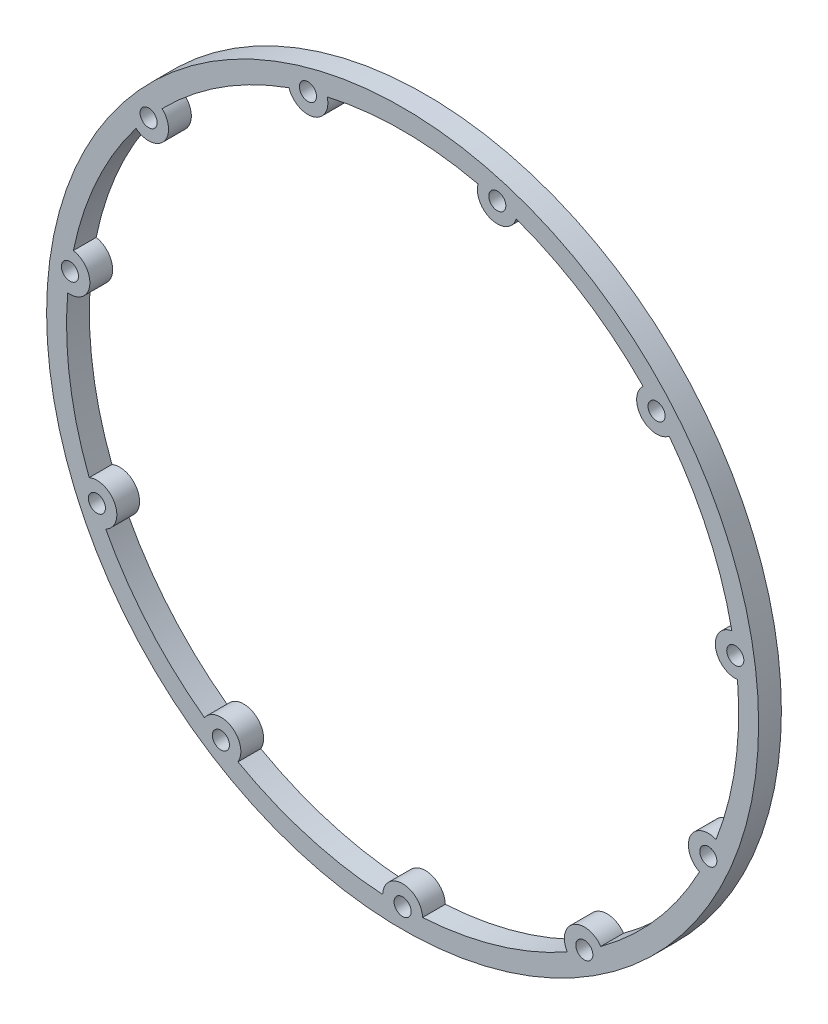
SolidWorks part; units mm, degrees
ref_plane "前视基准面" through (0, 0, 0) normal (0, 0, 1) x (1, 0, 0)
ref_plane "上视基准面" through (0, 0, 0) normal (0, 1, 0) x (1, 0, 0)
ref_plane "右视基准面" through (0, 0, 0) normal (1, 0, 0) x (0, 0, -1)
sketch "草图1" plane through (0, 0, 0) normal (0, 0, 1) x (1, 0, 0)
  line L0 (0, -59) -> (0, 0) construction
  line L1 (0, 0) -> (21.3581, 0) construction
  circle A1 centre (0, 0) radius 62.5
  circle A2 centre (0, 0) radius 59 construction
  circle A3 centre (0, -59) radius 1.5
  circle A4 centre (0, -59) radius 3.5 construction
  arc A5 (3.4985, -58.8962) -> (-3.4985, -58.8962) centre (0, -59) ccw
  circle A6 centre (-31.8978, -49.634) radius 1.5
  circle A7 centre (-53.6683, -24.5095) radius 1.5
  circle A8 centre (-58.3995, 8.3966) radius 1.5
  circle A9 centre (-44.5892, 38.6368) radius 1.5
  circle A10 centre (-16.6222, 56.6101) radius 1.5
  circle A11 centre (16.6222, 56.6101) radius 1.5
  circle A12 centre (44.5892, 38.6368) radius 1.5
  circle A13 centre (58.3995, 8.3966) radius 1.5
  circle A14 centre (53.6683, -24.5095) radius 1.5
  circle A15 centre (31.8978, -49.634) radius 1.5
  circle A16 centre (31.8978, -49.634) radius 3.5 construction
  arc A17 (28.8986, -51.438) -> (3.4985, -58.8962) centre (0, 0) cw
  arc A18 (-3.4985, -58.8962) -> (-28.8986, -51.438) centre (0, 0) cw
  arc A19 (-28.8986, -51.438) -> (-34.7848, -47.6552) centre (-31.8978, -49.634) ccw
  arc A20 (-34.7848, -47.6552) -> (-52.1205, -27.6487) centre (0, 0) cw
  arc A21 (-52.1205, -27.6487) -> (-55.0272, -21.284) centre (-53.6683, -24.5095) ccw
  arc A22 (-55.0272, -21.284) -> (-58.7946, 4.919) centre (0, 0) cw
  arc A23 (-58.7946, 4.919) -> (-57.7988, 11.8447) centre (-58.3995, 8.3966) ccw
  arc A24 (-57.7988, 11.8447) -> (-46.8018, 35.9248) centre (0, 0) cw
  arc A25 (-46.8018, 35.9248) -> (-42.2198, 41.2128) centre (-44.5892, 38.6368) ccw
  arc A26 (-42.2198, 41.2128) -> (-19.9497, 55.5248) centre (0, 0) cw
  arc A27 (-19.9497, 55.5248) -> (-13.2362, 57.4961) centre (-16.6222, 56.6101) ccw
  arc A28 (-13.2362, 57.4961) -> (13.2362, 57.4961) centre (0, 0) cw
  arc A29 (13.2362, 57.4961) -> (19.9497, 55.5248) centre (16.6222, 56.6101) ccw
  arc A30 (19.9497, 55.5248) -> (42.2198, 41.2128) centre (0, 0) cw
  arc A31 (42.2198, 41.2128) -> (46.8018, 35.9248) centre (44.5892, 38.6368) ccw
  arc A32 (46.8018, 35.9248) -> (57.7988, 11.8447) centre (0, 0) cw
  arc A33 (57.7988, 11.8447) -> (58.7946, 4.919) centre (58.3995, 8.3966) ccw
  arc A34 (58.7946, 4.919) -> (55.0272, -21.284) centre (0, 0) cw
  arc A35 (55.0272, -21.284) -> (52.1205, -27.6487) centre (53.6683, -24.5095) ccw
  arc A36 (52.1205, -27.6487) -> (34.7848, -47.6552) centre (0, 0) cw
  arc A37 (34.7848, -47.6552) -> (28.8986, -51.438) centre (31.8978, -49.634) ccw
  point P7 (0, 0)
  dimension "D1" = 11
  dimension "D2" = 125
  dimension "D3" = 118
  dimension "D4" = 3
  dimension "D5" = 11
extrude "凸台-拉伸1" add sketch "草图1" along normal blind 4 contours A4
